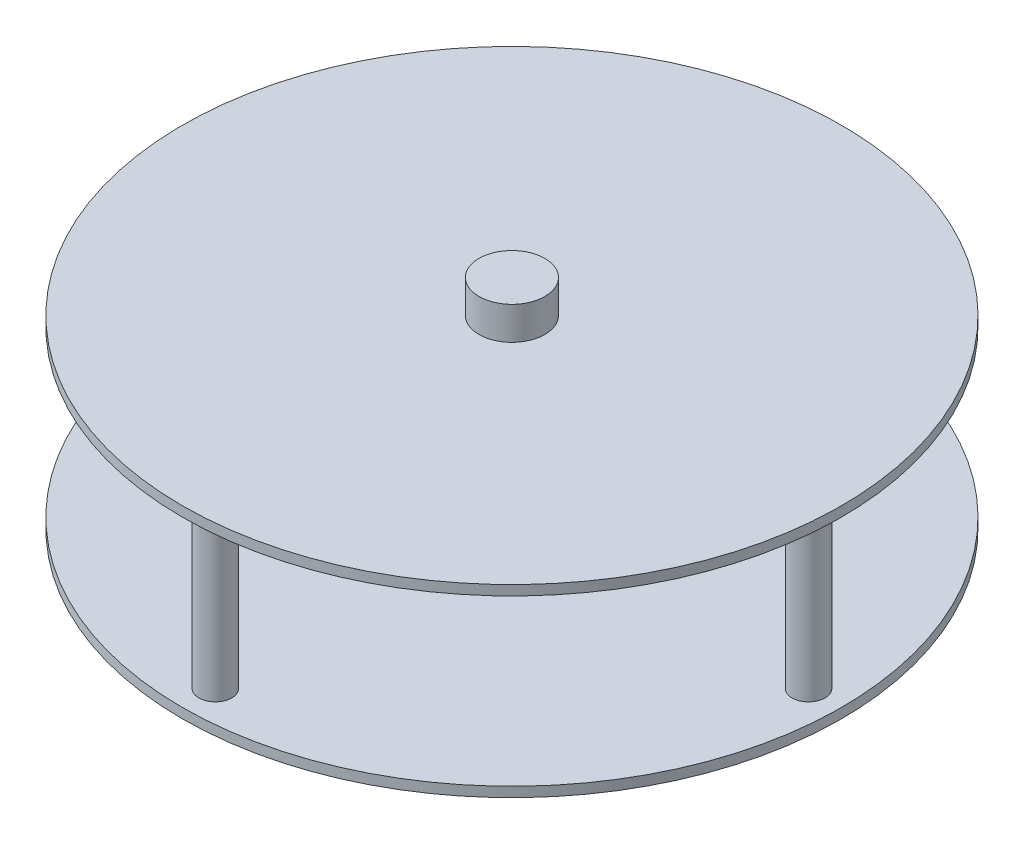
SolidWorks part; units mm, degrees
ref_plane "Front Plane" through (0, 0, 0) normal (0, 0, 1) x (1, 0, 0)
ref_plane "Top Plane" through (0, 0, 0) normal (0, 1, 0) x (1, 0, 0)
ref_plane "Right Plane" through (0, 0, 0) normal (1, 0, 0) x (0, 0, -1)
sketch "Sketch1" plane through (0, 0, 0) normal (0, 1, 0) x (1, 0, 0)
  circle A0 centre (0, 0) radius 100
  dimension "D1" = 200
extrude "Boss-Extrude1" add sketch "Sketch1" along normal blind 3
sketch "Sketch2" plane through (0, 3, 0) normal (0, 1, 0) x (1, 0, 0)
  circle A0 centre (-90, 0) radius 5
  circle A1 centre (0, 90) radius 5
  circle A2 centre (90, 0) radius 5
  circle A3 centre (0, -90) radius 5
  dimension "D1" = 10
  dimension "D2" = 90
  dimension "D3" = 90
  dimension "D4" = 90
  dimension "D5" = 90
extrude "Boss-Extrude2" add sketch "Sketch2" along normal blind 50
ref_plane "Plane1" through (0, 28, 0) normal (0, 1, 0) x (1, 0, 0)
mirror "Mirror1" about plane through (0, 28, 0) normal (0, 1, 0) of "Boss-Extrude1"
sketch "Sketch3" plane through (0, 56, 0) normal (0, 1, 0) x (1, 0, 0)
  circle A0 centre (0, 0) radius 10
  dimension "D1" = 20
extrude "Boss-Extrude3" add sketch "Sketch3" along normal blind 10
